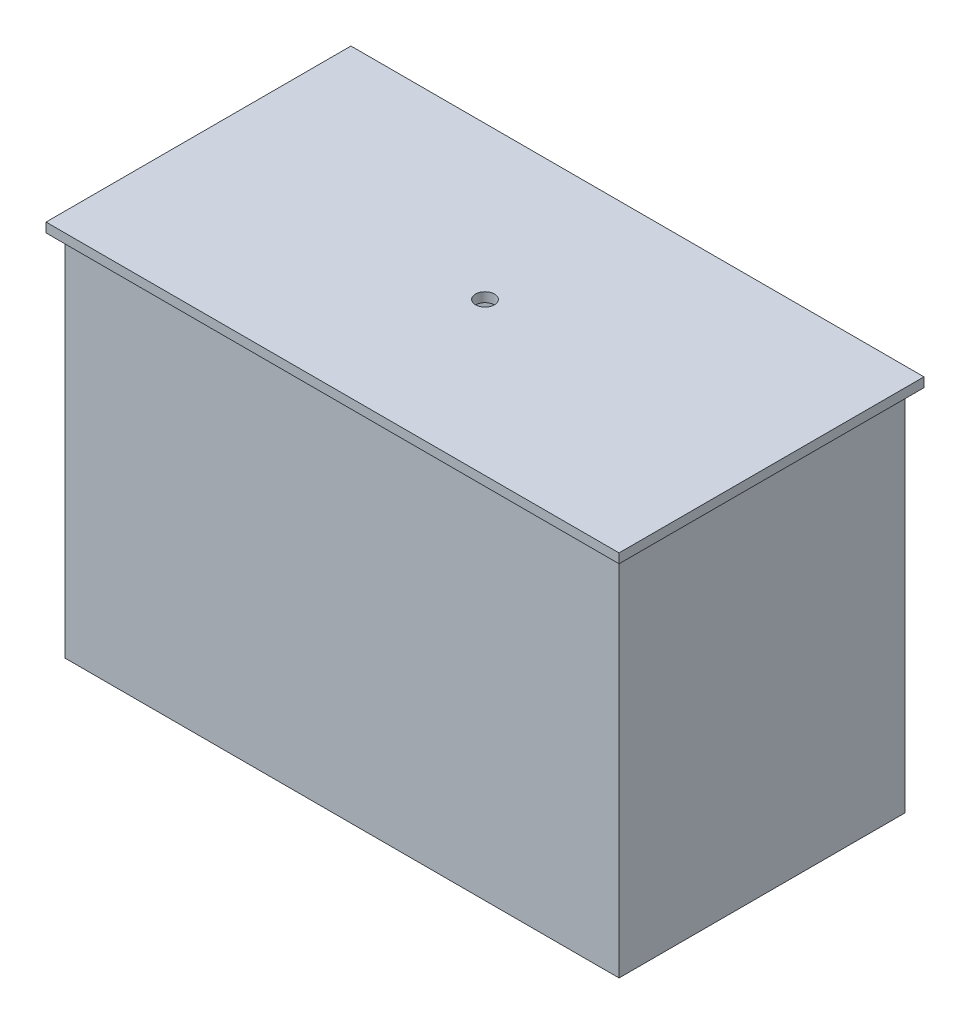
SolidWorks part; units mm, degrees
ref_plane "Front Plane" through (0, 0, 0) normal (0, 0, 1) x (1, 0, 0)
ref_plane "Top Plane" through (0, 0, 0) normal (0, 1, 0) x (1, 0, 0)
ref_plane "Right Plane" through (0, 0, 0) normal (1, 0, 0) x (0, 0, -1)
sketch "Sketch2" plane through (0, 0, 0) normal (0, 1, 0) x (1, 0, 0)
  line L1 (-293.5, 151.5) -> (293.5, 151.5)
  line L2 (-293.5, 151.5) -> (-293.5, -151.5)
  line L3 (-293.5, -151.5) -> (293.5, -151.5)
  line L4 (293.5, 151.5) -> (293.5, -151.5)
  line L5 (-293.5, 151.5) -> (293.5, -151.5) construction
  line L6 (-293.5, -151.5) -> (293.5, 151.5) construction
  point P0 (0, 0)
  dimension "D1" = 303
  dimension "D2" = 587
extrude "Base" add sketch "Sketch2" along normal blind 10
sketch "Sketch4" plane through (0, 10, 0) normal (0, 1, 0) x (1, 0, 0)
  line L4 (-293.5, -151.5) -> (293.5, -151.5) construction
  line L5 (293.5, -151.5) -> (293.5, 151.5) construction
  line L6 (293.5, 151.5) -> (-293.5, 151.5) construction
  line L7 (-293.5, 151.5) -> (-293.5, -151.5) construction
  line L8 (283.5, -141.5) -> (283.5, 141.5)
  line L9 (283.5, 141.5) -> (-283.5, 141.5)
  line L10 (-283.5, 141.5) -> (-283.5, -141.5)
  line L11 (-283.5, -141.5) -> (283.5, -141.5)
  line L12 (283.5, -141.5) -> (283.5, 141.5)
  line L13 (283.5, 141.5) -> (-283.5, 141.5)
  line L14 (-283.5, 141.5) -> (-283.5, -141.5)
  line L15 (-283.5, -141.5) -> (283.5, -141.5)
  line L16 (-293.5, -151.5) -> (293.5, -151.5)
  line L17 (293.5, -151.5) -> (293.5, 151.5)
  line L18 (293.5, 151.5) -> (-293.5, 151.5)
  line L19 (-293.5, 151.5) -> (-293.5, -151.5)
  dimension "D1" = 10
extrude "Walls" add sketch "Sketch4" along normal blind 380
sketch "Sketch5" plane through (-293.5, 0, 0) normal (-1, 0, 0) x (0, 0, 1)
  line L0 (-151.5, 390) -> (151.5, 390) construction
  line L1 (-161.5, 390) -> (161.5, 390)
  line L2 (-161.5, 390) -> (-161.5, 400)
  line L3 (-161.5, 400) -> (161.5, 400)
  line L4 (161.5, 390) -> (161.5, 400)
  line L5 (-161.5, 390) -> (161.5, 400) construction
  line L6 (-161.5, 400) -> (161.5, 390) construction
  point P4 (0, 395)
  dimension "D1" = 10
  dimension "D2" = 10
  dimension "D3" = 10
extrude "Lid" add sketch "Sketch5" against normal blind 597 and the other way blind 10
sketch "Sketch8" plane through (0, 400, 0) normal (0, 1, 0) x (1, 0, 0)
  circle A0 centre (0, 0) radius 10
  dimension "D1" = 20
extrude "Inlet" cut sketch "Sketch8" against normal up to next
sketch "Sketch9" plane through (0, 0, 0) normal (0, -1, 0) x (1, 0, 0)
  line L0 (-293.5, -151.5) -> (-293.5, 151.5) construction
  circle A0 centre (-248.5, 0) radius 10
  dimension "D1" = 20
  dimension "D2" = 45
extrude "Outlet" cut sketch "Sketch9" against normal up to next
equation "\"D1@Walls\" = 390 - 10"
equation "\"D1@Lid\" = 587.00mm + 10"
